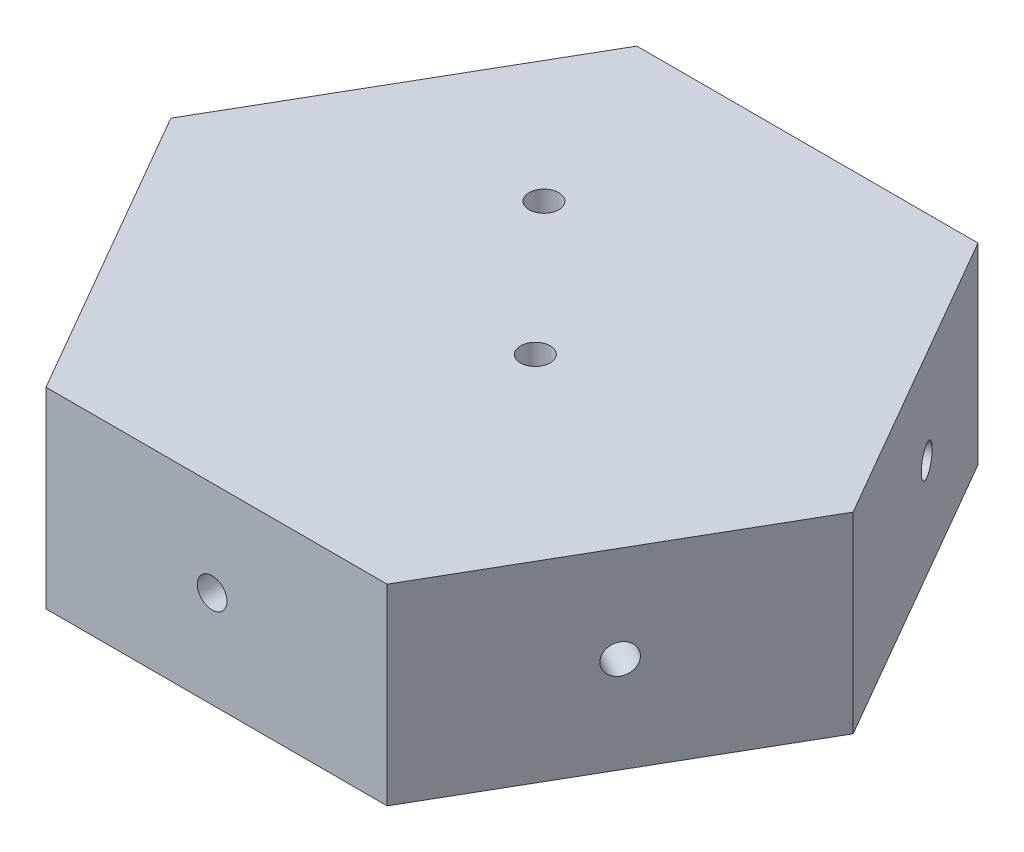
SolidWorks part; units mm, degrees
ref_plane "Front Plane" through (0, 0, 0) normal (0, 0, 1) x (1, 0, 0)
ref_plane "Top Plane" through (0, 0, 0) normal (0, 1, 0) x (1, 0, 0)
ref_plane "Right Plane" through (0, 0, 0) normal (1, 0, 0) x (0, 0, -1)
sketch "Sketch1" plane through (0, 0, 0) normal (0, 1, 0) x (1, 0, 0)
  line L0 (-58.6588, 0) -> (-29.3294, -50.8)
  line L1 (58.6588, 0) -> (29.3294, 50.8)
  line L2 (29.3294, 50.8) -> (-29.3294, 50.8)
  line L3 (-29.3294, 50.8) -> (-58.6588, 0)
  line L4 (-29.3294, -50.8) -> (29.3294, -50.8)
  line L5 (29.3294, -50.8) -> (58.6588, 0)
  circle A0 centre (0, 0) radius 50.8 construction
  dimension "D1" = 101.6
extrude "Boss-Extrude1" add sketch "Sketch1" along normal mid plane 33.02
sketch "Sketch5" plane through (43.9941, 0, 25.4) normal (0.866, 0, 0.5) x (0.5, 0, -0.866)
  line L0 (-29.3294, -16.51) -> (29.3294, 16.51) construction
hole_wizard "1/4-20 Tapped Hole2" positions "3DSketch1" profile "Sketch4" tap size "1/4-20" standard "ANSI Inch"
sketch3d "3DSketch1"
  line L0 (29.3294, -16.51, 50.8) -> (58.6588, 16.51, 0) construction
  point P0 (-14.2252, 16.51, -19.7174)
  point P2 (41.3695, 0.5624, -29.9459)
  point P4 (43.9941, 0, 25.4)
  point P6 (-0.7672, 0.172, 50.8)
  point P8 (-38.1907, -1.7307, 35.4518)
  point P10 (-48.0314, -4.7452, -18.4072)
  point P12 (3.4901, -2.9166, -50.8)
  point P14 (7.8545, 16.51, 3.8397)
  point P18 (43.9941, 0, 25.4)
sketch "Sketch4" plane through (-14.2252, 16.51, -19.7174) normal (1, 0, 0) x (0, 0, 1)
  line L0 (0, 0) -> (0, 18.0438)
  line L1 (0, 18.0438) -> (2.5527, 16.51)
  line L2 (2.5527, 16.51) -> (2.5527, 0)
  line L5 (2.5527, 0) -> (0, 0)
  line L10 (0, 18.0438) -> (-2.5527, 16.51) construction
  line L11 (0, -6.35) -> (0, 107.95) construction
  dimension "Tap Drill Dia." = 5.1054
  dimension "Tap Drill Depth" = 16.51
  dimension "Drill Angle" = 118
cosmetic thread "Hole Thread4" parameters "D1"=12.7, "D2"=6.35
cosmetic thread "Hole Thread5" parameters "D1"=12.7, "D2"=6.35
cosmetic thread "Hole Thread6" parameters "D1"=12.7, "D2"=6.35
cosmetic thread "Hole Thread7" parameters "D1"=12.7, "D2"=6.35
cosmetic thread "Hole Thread8" parameters "D1"=12.7, "D2"=6.35
cosmetic thread "Hole Thread9" parameters "D1"=12.7, "D2"=6.35
cosmetic thread "Hole Thread10" parameters "D1"=12.7, "D2"=6.35
cosmetic thread "Hole Thread11" parameters "D1"=12.7, "D2"=6.35
